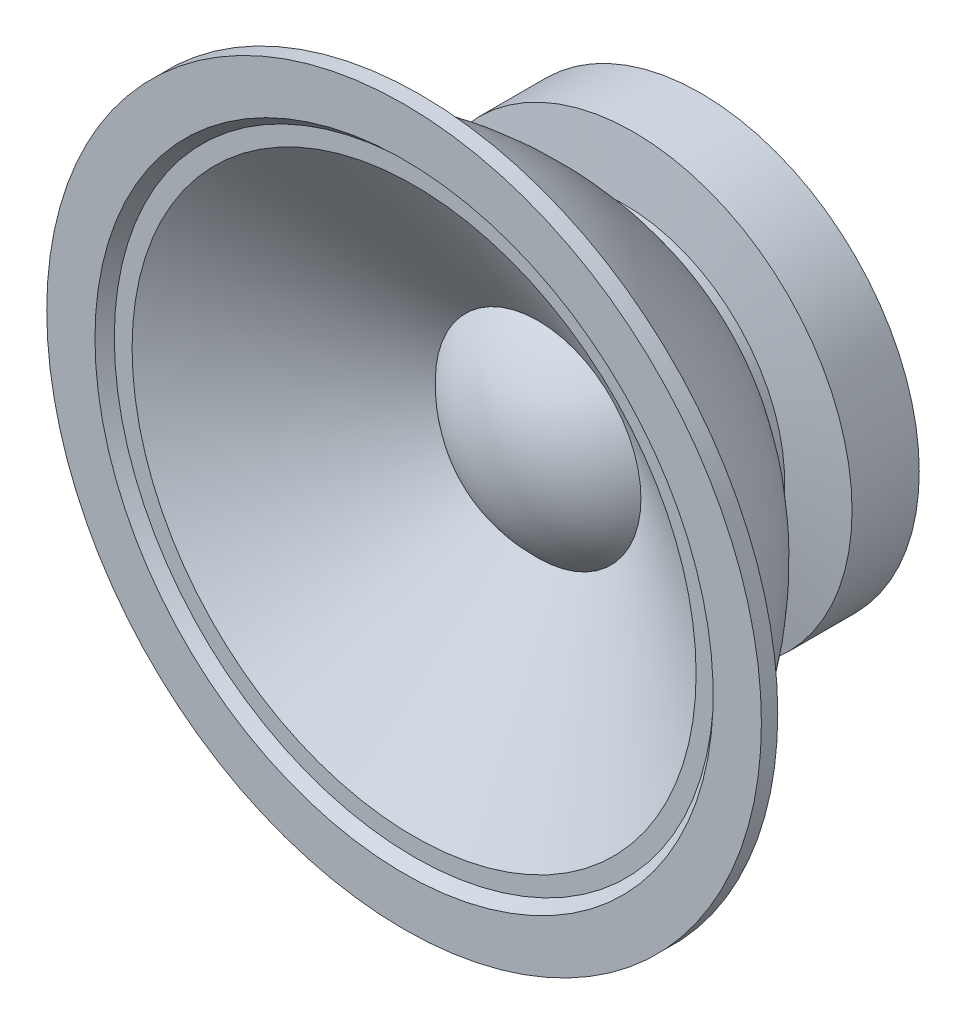
SolidWorks part; units mm, degrees
ref_plane "Front Plane" through (0, 0, 0) normal (0, 0, 1) x (1, 0, 0)
ref_plane "Top Plane" through (0, 0, 0) normal (0, 1, 0) x (1, 0, 0)
ref_plane "Right Plane" through (0, 0, 0) normal (1, 0, 0) x (0, 0, -1)
sketch "Sketch1" plane through (0, 0, 0) normal (0, 1, 0) x (1, 0, 0)
  line L0 (0, 0) -> (0, 173.99) construction
  line L1 (0, 173.99) -> (34.4414, 173.99)
  line L2 (34.4414, 173.99) -> (120.3628, 163.4451)
  line L3 (120.3628, 163.4451) -> (120.3628, 126.418)
  line L4 (120.3628, 126.418) -> (87.9302, 121.7175)
  line L5 (87.9302, 121.7175) -> (87.9302, 116.4893)
  line L6 (87.9302, 116.4893) -> (176.53, 9.0078) construction
  line L7 (176.53, 9.0078) -> (196.85, 9.0078)
  line L8 (196.85, 9.0078) -> (196.85, 0)
  line L9 (196.85, 0) -> (0, 0) construction
  line L10 (0, 173.99) -> (0, 49.1528)
  line L11 (196.85, 0) -> (170.2875, 0)
  line L12 (170.2875, 0) -> (165.1461, 5.519)
  line L13 (165.1461, 5.519) -> (155.3572, 5.519)
  line L14 (155.3572, 5.519) -> (56.635, 73.8595)
  line L15 (0, 49.1528) -> (220.5629, 49.1528) construction
  arc A0 (56.635, 73.8595) -> (0, 49.1528) centre (0, 126.418) cw
  arc A1 (87.9302, 116.4893) -> (176.53, 9.0078) centre (-32.0994, -72.7126) cw
  point P12 (165.1773, 23.4419)
  point P18 (165.1461, 5.519)
  point P20 (170.2875, 0)
  point P21 (89.4592, 96.1441)
  point P22 (89.4592, 103.9114)
  point P23 (120.3628, 126.418)
  point P24 (97.5294, 97.382)
  point P25 (97.5294, 119.0937)
  point P26 (97.5294, 115.9587)
  point P27 (82.183, 110.6635)
  point P29 (82.183, 121.7175)
  point P30 (82.183, 116.4893)
  dimension "D1" = 173.99
  dimension "D2" = 196.85
  dimension "D3" = 176.53
revolve "Revolve1" add sketch "Sketch1" angle 360 about L10
